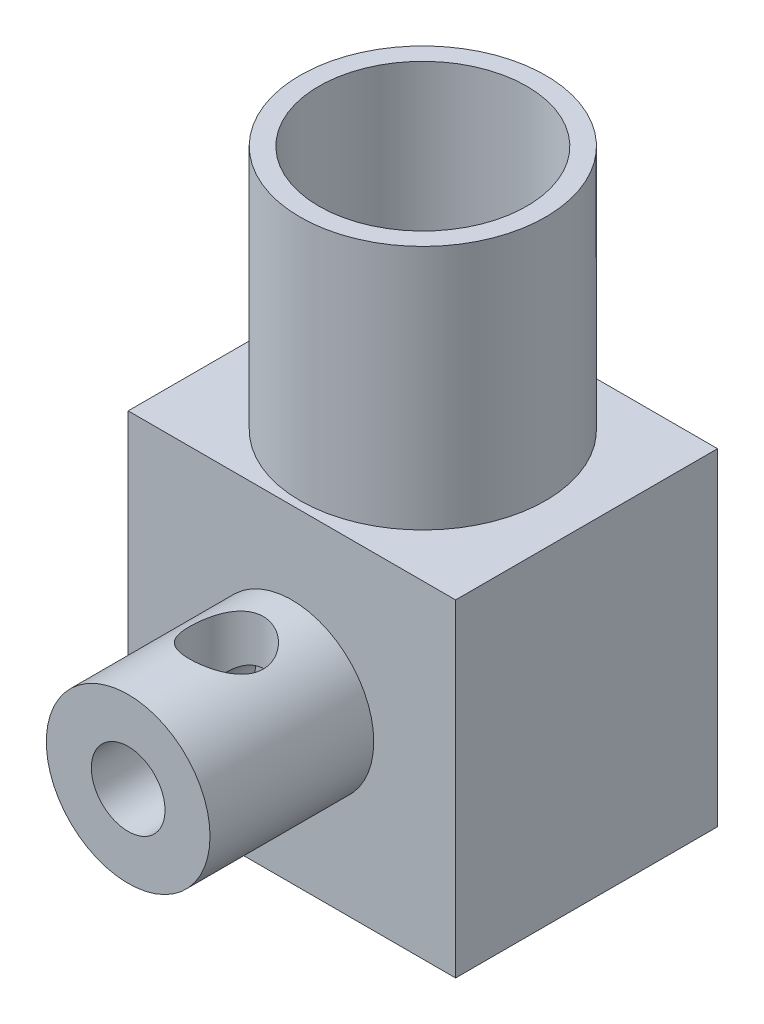
SolidWorks part; units mm, degrees
ref_plane "Alzado" through (0, 0, 0) normal (0, 0, 1) x (1, 0, 0)
ref_plane "Planta" through (0, 0, 0) normal (0, 1, 0) x (1, 0, 0)
ref_plane "Vista lateral" through (0, 0, 0) normal (1, 0, 0) x (0, 0, -1)
sketch "Croquis1" plane through (0, 0, 0) normal (0, 0, 1) x (1, 0, 0)
  line L1 (-10, -10) -> (10, -10)
  line L2 (-10, -10) -> (-10, 10)
  line L3 (-10, 10) -> (10, 10)
  line L4 (10, -10) -> (10, 10)
  line L5 (-10, -10) -> (10, 10) construction
  line L6 (-10, 10) -> (10, -10) construction
  point P0 (0, 0)
  dimension "D1" = 20
  dimension "D2" = 20
extrude "Saliente-Extruir1" add sketch "Croquis1" along normal blind 16
sketch "Croquis2" plane through (0, 0, 16) normal (0, 0, 1) x (1, 0, 0)
  circle A0 centre (0, 0) radius 5
  circle A1 centre (0, 0) radius 2.25
  dimension "D1" = 10
  dimension "D2" = 4.5
extrude "Saliente-Extruir2" add sketch "Croquis2" along normal blind 10
sketch "Croquis6" plane through (0, 10, 0) normal (0, 1, 0) x (1, 0, 0)
  line L0 (-10, -16) -> (-10, 0) construction
  line L1 (10, -16) -> (-10, -16) construction
  circle A0 centre (0, -8) radius 6.35
  circle A1 centre (0, -8) radius 7.5
  dimension "D1" = 15
  dimension "D2" = 12.7
  dimension "D3" = 10
  dimension "D4" = 8
extrude "Saliente-Extruir3" add sketch "Croquis6" along normal blind 15
sketch "Croquis7" plane through (0, 10, 0) normal (0, 1, 0) x (1, 0, 0)
  circle A0 centre (0, -20) radius 2.25
  dimension "D1" = 4.5
  dimension "D2" = 20
extrude "Cortar-Extruir1" cut sketch "Croquis7" against normal blind 10
